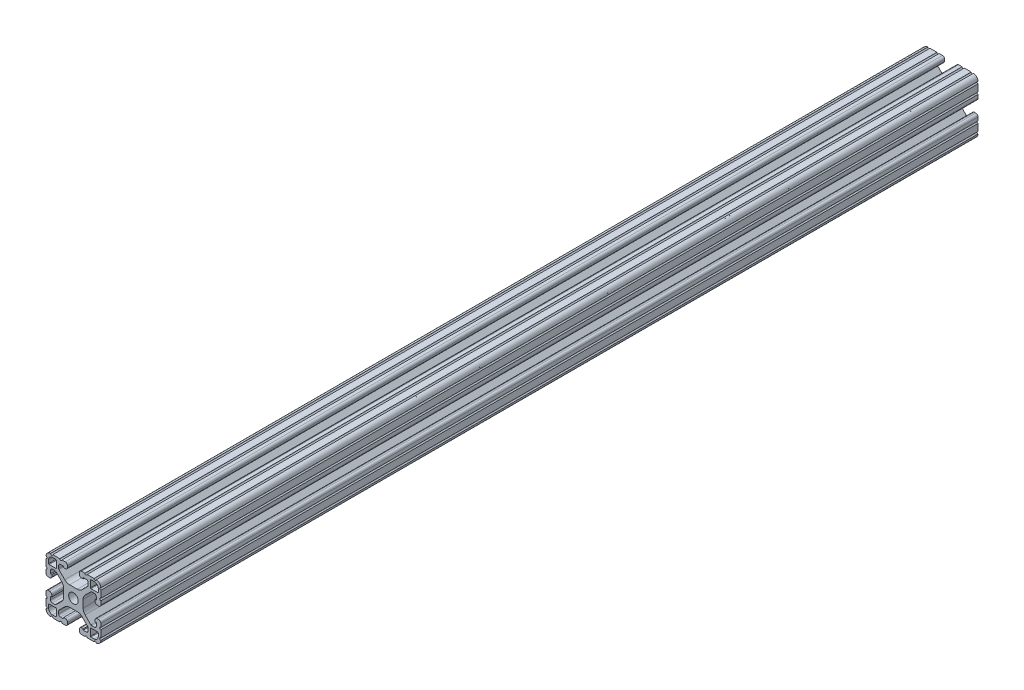
SolidWorks part; units mm, degrees
material "6061 Alloy"
ref_plane "Front Plane" through (0, 0, 0) normal (0, 0, 1) x (1, 0, 0)
ref_plane "Top Plane" through (0, 0, 0) normal (0, 1, 0) x (1, 0, 0)
ref_plane "Right Plane" through (0, 0, 0) normal (1, 0, 0) x (0, 0, -1)
sketch "Sketch1" plane through (0, 0, 0) normal (0, 0, 1) x (1, 0, 0)
  line L0 (0, 21.507) -> (0, -20.9529) construction
  line L1 (20.4424, 0) -> (-20.8151, 0) construction
  line L2 (10.0267, -12.1519) -> (6.0215, -8.1473)
  line L3 (-10.0267, 12.1519) -> (-6.0215, 8.1473)
  line L4 (-10.287, 14.5547) -> (-10.287, 12.7802)
  line L5 (-6.8141, 15.8247) -> (-9.017, 15.8247)
  line L6 (10.287, -14.5547) -> (10.287, -12.7802)
  line L7 (-6.8141, 14.986) -> (-6.8141, 15.8247)
  line L8 (6.8141, -15.8247) -> (9.017, -15.8247)
  line L9 (-2.6631, -6.7564) -> (2.6631, -6.7564)
  line L10 (6.8141, -14.986) -> (6.8141, -15.8247)
  line L11 (5.6388, -14.986) -> (6.8141, -14.986)
  line L12 (4.064, -17.4752) -> (4.064, -16.5608)
  line L13 (7.9756, -19.05) -> (5.6388, -19.05)
  line L14 (14.3256, -19.05) -> (9.4996, -19.05)
  line L15 (15.875, -19.05) -> (15.8496, -19.05)
  line L16 (19.05, -15.8496) -> (19.05, -15.875)
  line L17 (19.05, -9.4996) -> (19.05, -14.3256)
  line L18 (19.05, -5.6388) -> (19.05, -7.9756)
  line L19 (-5.6388, 14.986) -> (-6.8141, 14.986)
  line L20 (-4.064, 17.4752) -> (-4.064, 16.5608)
  line L21 (-7.9756, 19.05) -> (-5.6388, 19.05)
  line L22 (16.5608, -4.064) -> (17.4752, -4.064)
  line L23 (-14.3256, 19.05) -> (-9.4996, 19.05)
  line L24 (14.986, -6.7506) -> (14.986, -5.6388)
  line L25 (15.879, -6.7506) -> (14.986, -6.7506)
  line L26 (-15.875, 19.05) -> (-15.8496, 19.05)
  line L27 (-19.05, 15.8496) -> (-19.05, 15.875)
  line L28 (15.879, -8.9192) -> (15.879, -6.7506)
  line L29 (12.7428, -10.1892) -> (14.609, -10.1892)
  line L30 (-19.05, 9.4996) -> (-19.05, 14.3256)
  line L31 (-19.05, 5.6388) -> (-19.05, 7.9756)
  line L32 (8.1479, -5.9632) -> (12.1142, -9.9289)
  line L33 (16.891, -11.8618) -> (12.2428, -11.8618)
  line L34 (11.8618, -12.2428) -> (11.8618, -16.891)
  line L35 (12.2428, -17.272) -> (14.478, -17.272)
  line L36 (17.272, 14.478) -> (17.272, 12.2428)
  line L37 (12.2428, 17.272) -> (14.478, 17.272)
  line L38 (11.8618, 12.2428) -> (11.8618, 16.891)
  line L39 (16.891, 11.8618) -> (12.2428, 11.8618)
  line L40 (17.272, -14.478) -> (17.272, -12.2428)
  line L41 (-16.5608, 4.064) -> (-17.4752, 4.064)
  line L42 (-14.986, 6.7506) -> (-14.986, 5.6388)
  line L43 (-15.879, 6.7506) -> (-14.986, 6.7506)
  line L44 (-15.879, 8.9192) -> (-15.879, 6.7506)
  line L45 (-12.7428, 10.1892) -> (-14.609, 10.1892)
  line L46 (-8.1479, 5.9632) -> (-12.1142, 9.9289)
  line L47 (-6.7564, -2.6043) -> (-6.7564, 2.6043)
  line L48 (-17.272, -14.478) -> (-17.272, -12.2428)
  line L49 (-16.891, 11.8618) -> (-12.2428, 11.8618)
  line L50 (-11.8618, 12.2428) -> (-11.8618, 16.891)
  line L51 (-12.2428, 17.272) -> (-14.478, 17.272)
  line L52 (-17.272, 14.478) -> (-17.272, 12.2428)
  line L53 (-12.2428, -17.272) -> (-14.478, -17.272)
  line L54 (-11.8618, -12.2428) -> (-11.8618, -16.891)
  line L55 (-16.891, -11.8618) -> (-12.2428, -11.8618)
  line L56 (-8.1479, -5.9632) -> (-12.1142, -9.9289)
  line L57 (-12.7428, -10.1892) -> (-14.609, -10.1892)
  line L58 (-15.879, -8.9192) -> (-15.879, -6.7506)
  line L59 (-15.879, -6.7506) -> (-14.986, -6.7506)
  line L60 (-14.986, -6.7506) -> (-14.986, -5.6388)
  line L61 (-16.5608, -4.064) -> (-17.4752, -4.064)
  line L62 (-19.05, -5.6388) -> (-19.05, -7.9756)
  line L63 (-19.05, -9.4996) -> (-19.05, -14.3256)
  line L64 (-19.05, -15.8496) -> (-19.05, -15.875)
  line L65 (-15.875, -19.05) -> (-15.8496, -19.05)
  line L66 (-14.3256, -19.05) -> (-9.4996, -19.05)
  line L67 (-7.9756, -19.05) -> (-5.6388, -19.05)
  line L68 (-4.064, -17.4752) -> (-4.064, -16.5608)
  line L69 (-5.6388, -14.986) -> (-6.8141, -14.986)
  line L70 (-6.8141, -14.986) -> (-6.8141, -15.8247)
  line L71 (-6.8141, -15.8247) -> (-9.017, -15.8247)
  line L72 (-10.287, -14.5547) -> (-10.287, -12.7802)
  line L73 (-10.0267, -12.1519) -> (-6.0215, -8.1473)
  line L95 (6.7564, -2.6043) -> (6.7564, 2.6043)
  line L96 (8.1479, 5.9632) -> (12.1142, 9.9289)
  line L97 (12.7428, 10.1892) -> (14.609, 10.1892)
  line L98 (15.879, 8.9192) -> (15.879, 6.7506)
  line L99 (15.879, 6.7506) -> (14.986, 6.7506)
  line L100 (14.986, 6.7506) -> (14.986, 5.6388)
  line L101 (16.5608, 4.064) -> (17.4752, 4.064)
  line L102 (19.05, 5.6388) -> (19.05, 7.9756)
  line L103 (19.05, 9.4996) -> (19.05, 14.3256)
  line L104 (19.05, 15.8496) -> (19.05, 15.875)
  line L105 (15.875, 19.05) -> (15.8496, 19.05)
  line L106 (14.3256, 19.05) -> (9.4996, 19.05)
  line L107 (7.9756, 19.05) -> (5.6388, 19.05)
  line L108 (4.064, 17.4752) -> (4.064, 16.5608)
  line L109 (5.6388, 14.986) -> (6.8141, 14.986)
  line L110 (6.8141, 14.986) -> (6.8141, 15.8247)
  line L111 (6.8141, 15.8247) -> (9.017, 15.8247)
  line L112 (10.287, 14.5547) -> (10.287, 12.7802)
  line L113 (10.0267, 12.1519) -> (6.0215, 8.1473)
  line L114 (2.6631, 6.7564) -> (-2.6631, 6.7564)
  arc A0 (10.0267, -12.1519) -> (10.287, -12.7802) centre (9.3985, -12.7802) cw
  arc A1 (10.287, -14.5547) -> (9.017, -15.8247) centre (9.017, -14.5547) cw
  arc A2 (4.064, -16.5608) -> (5.6388, -14.986) centre (5.6388, -16.5608) cw
  arc A3 (-10.0267, 12.1519) -> (-10.287, 12.7802) centre (-9.3985, 12.7802) cw
  arc A4 (-10.287, 14.5547) -> (-9.017, 15.8247) centre (-9.017, 14.5547) cw
  arc A5 (5.6388, -19.05) -> (4.064, -17.4752) centre (5.6388, -17.4752) cw
  arc A6 (7.9756, -19.05) -> (9.4996, -19.05) centre (8.7376, -19.05) cw
  arc A7 (-4.064, 16.5608) -> (-5.6388, 14.986) centre (-5.6388, 16.5608) cw
  arc A8 (14.3256, -19.05) -> (15.8496, -19.05) centre (15.0876, -19.05) cw
  arc A9 (19.05, -15.875) -> (15.875, -19.05) centre (15.875, -15.875) cw
  arc A10 (6.0215, -8.1473) -> (2.6631, -6.7564) centre (2.6631, -11.5062) ccw
  arc A11 (-6.0215, -8.1473) -> (-2.6631, -6.7564) centre (-2.6631, -11.5062) cw
  arc A12 (19.05, -15.8496) -> (19.05, -14.3256) centre (19.05, -15.0876) cw
  arc A13 (19.05, -9.4996) -> (19.05, -7.9756) centre (19.05, -8.7376) cw
  arc A14 (17.4752, -4.064) -> (19.05, -5.6388) centre (17.4752, -5.6388) cw
  arc A15 (14.986, -5.6388) -> (16.5608, -4.064) centre (16.5608, -5.6388) cw
  arc A16 (15.879, -8.9192) -> (14.609, -10.1892) centre (14.609, -8.9192) cw
  arc A17 (12.7428, -10.1892) -> (12.1142, -9.9289) centre (12.7428, -9.3002) cw
  arc A18 (16.891, -11.8618) -> (17.272, -12.2428) centre (16.891, -12.2428) cw
  arc A19 (-5.6388, 19.05) -> (-4.064, 17.4752) centre (-5.6388, 17.4752) cw
  arc A20 (-7.9756, 19.05) -> (-9.4996, 19.05) centre (-8.7376, 19.05) cw
  arc A21 (-14.3256, 19.05) -> (-15.8496, 19.05) centre (-15.0876, 19.05) cw
  arc A22 (11.8618, -12.2428) -> (12.2428, -11.8618) centre (12.2428, -12.2428) cw
  arc A23 (-19.05, 15.875) -> (-15.875, 19.05) centre (-15.875, 15.875) cw
  arc A24 (12.2428, -17.272) -> (11.8618, -16.891) centre (12.2428, -16.891) cw
  arc A25 (17.272, -14.478) -> (14.478, -17.272) centre (14.478, -14.478) cw
  arc A26 (-19.05, 15.8496) -> (-19.05, 14.3256) centre (-19.05, 15.0876) cw
  arc A27 (-19.05, 9.4996) -> (-19.05, 7.9756) centre (-19.05, 8.7376) cw
  arc A28 (-17.4752, 4.064) -> (-19.05, 5.6388) centre (-17.4752, 5.6388) cw
  arc A29 (-14.986, 5.6388) -> (-16.5608, 4.064) centre (-16.5608, 5.6388) cw
  arc A30 (-15.879, 8.9192) -> (-14.609, 10.1892) centre (-14.609, 8.9192) cw
  arc A31 (-12.7428, 10.1892) -> (-12.1142, 9.9289) centre (-12.7428, 9.3002) cw
  arc A32 (-8.1479, 5.9632) -> (-6.7564, 2.6043) centre (-11.5062, 2.6043) cw
  arc A33 (-6.7564, -2.6043) -> (-8.1479, -5.9632) centre (-11.5062, -2.6043) cw
  arc A34 (-16.891, 11.8618) -> (-17.272, 12.2428) centre (-16.891, 12.2428) cw
  arc A35 (-11.8618, 12.2428) -> (-12.2428, 11.8618) centre (-12.2428, 12.2428) cw
  arc A36 (17.272, 14.478) -> (14.478, 17.272) centre (14.478, 14.478) ccw
  arc A37 (12.2428, 17.272) -> (11.8618, 16.891) centre (12.2428, 16.891) ccw
  arc A38 (11.8618, 12.2428) -> (12.2428, 11.8618) centre (12.2428, 12.2428) ccw
  arc A39 (16.891, 11.8618) -> (17.272, 12.2428) centre (16.891, 12.2428) ccw
  arc A40 (-12.2428, 17.272) -> (-11.8618, 16.891) centre (-12.2428, 16.891) cw
  circle A41 centre (0, 0) radius 3.3274
  arc A42 (-17.272, 14.478) -> (-14.478, 17.272) centre (-14.478, 14.478) cw
  arc A43 (-17.272, -14.478) -> (-14.478, -17.272) centre (-14.478, -14.478) ccw
  arc A44 (-12.2428, -17.272) -> (-11.8618, -16.891) centre (-12.2428, -16.891) ccw
  arc A45 (-11.8618, -12.2428) -> (-12.2428, -11.8618) centre (-12.2428, -12.2428) ccw
  arc A46 (-16.891, -11.8618) -> (-17.272, -12.2428) centre (-16.891, -12.2428) ccw
  arc A47 (-12.7428, -10.1892) -> (-12.1142, -9.9289) centre (-12.7428, -9.3002) ccw
  arc A48 (-15.879, -8.9192) -> (-14.609, -10.1892) centre (-14.609, -8.9192) ccw
  arc A49 (-14.986, -5.6388) -> (-16.5608, -4.064) centre (-16.5608, -5.6388) ccw
  arc A50 (-17.4752, -4.064) -> (-19.05, -5.6388) centre (-17.4752, -5.6388) ccw
  arc A51 (-19.05, -9.4996) -> (-19.05, -7.9756) centre (-19.05, -8.7376) ccw
  arc A52 (-19.05, -15.8496) -> (-19.05, -14.3256) centre (-19.05, -15.0876) ccw
  arc A53 (-19.05, -15.875) -> (-15.875, -19.05) centre (-15.875, -15.875) ccw
  arc A54 (-14.3256, -19.05) -> (-15.8496, -19.05) centre (-15.0876, -19.05) ccw
  arc A55 (-7.9756, -19.05) -> (-9.4996, -19.05) centre (-8.7376, -19.05) ccw
  arc A56 (-5.6388, -19.05) -> (-4.064, -17.4752) centre (-5.6388, -17.4752) ccw
  arc A57 (-4.064, -16.5608) -> (-5.6388, -14.986) centre (-5.6388, -16.5608) ccw
  arc A58 (-10.287, -14.5547) -> (-9.017, -15.8247) centre (-9.017, -14.5547) ccw
  arc A59 (-10.0267, -12.1519) -> (-10.287, -12.7802) centre (-9.3985, -12.7802) ccw
  arc A86 (6.7564, -2.6043) -> (8.1479, -5.9632) centre (11.5062, -2.6043) ccw
  arc A87 (8.1479, 5.9632) -> (6.7564, 2.6043) centre (11.5062, 2.6043) ccw
  arc A88 (12.7428, 10.1892) -> (12.1142, 9.9289) centre (12.7428, 9.3002) ccw
  arc A89 (15.879, 8.9192) -> (14.609, 10.1892) centre (14.609, 8.9192) ccw
  arc A90 (14.986, 5.6388) -> (16.5608, 4.064) centre (16.5608, 5.6388) ccw
  arc A91 (17.4752, 4.064) -> (19.05, 5.6388) centre (17.4752, 5.6388) ccw
  arc A92 (19.05, 9.4996) -> (19.05, 7.9756) centre (19.05, 8.7376) ccw
  arc A93 (19.05, 15.8496) -> (19.05, 14.3256) centre (19.05, 15.0876) ccw
  arc A94 (19.05, 15.875) -> (15.875, 19.05) centre (15.875, 15.875) ccw
  arc A95 (14.3256, 19.05) -> (15.8496, 19.05) centre (15.0876, 19.05) ccw
  arc A96 (7.9756, 19.05) -> (9.4996, 19.05) centre (8.7376, 19.05) ccw
  arc A97 (5.6388, 19.05) -> (4.064, 17.4752) centre (5.6388, 17.4752) ccw
  arc A98 (4.064, 16.5608) -> (5.6388, 14.986) centre (5.6388, 16.5608) ccw
  arc A99 (10.287, 14.5547) -> (9.017, 15.8247) centre (9.017, 14.5547) ccw
  arc A100 (10.0267, 12.1519) -> (10.287, 12.7802) centre (9.3985, 12.7802) ccw
  arc A101 (2.6631, 6.7564) -> (6.0215, 8.1473) centre (2.6631, 11.5062) ccw
  arc A102 (-6.0215, 8.1473) -> (-2.6631, 6.7564) centre (-2.6631, 11.5062) ccw
  dimension "D1" = 6.6548
  dimension "D2" = 38.1
  dimension "D3" = 20.574
  dimension "D4" = 12.2936
  dimension "D5" = 19.05
  dimension "D6" = 8.128
  dimension "D7" = 3.048
  dimension "D8" = 4.064
  dimension "D9" = 13.5128
extrude "Extrude1" add sketch "Sketch1" against normal blind 609.6
